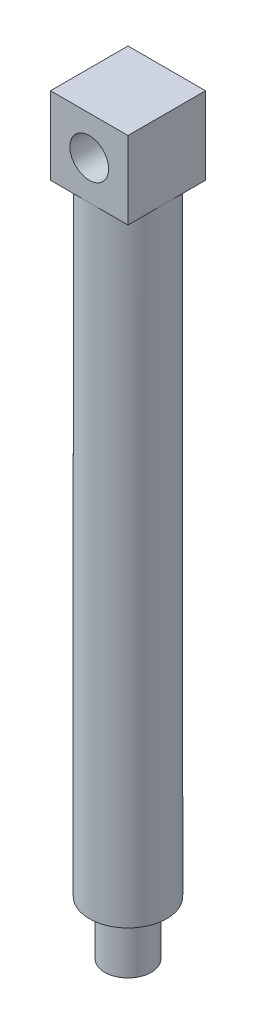
SolidWorks part; units mm, degrees
ref_plane "Front Plane" through (0, 0, 0) normal (0, 0, 1) x (1, 0, 0)
ref_plane "Top Plane" through (0, 0, 0) normal (0, 1, 0) x (1, 0, 0)
ref_plane "Right Plane" through (0, 0, 0) normal (1, 0, 0) x (0, 0, -1)
sketch "Sketch2" plane through (0, 0, 0) normal (0, 0, 1) x (1, 0, 0)
  line L0 (0, 0) -> (0, 10)
  line L1 (0, 10) -> (10, 10)
  line L2 (10, 10) -> (10, 0)
  line L3 (0, 0) -> (10, 0)
  point P6 (3.3156, 0)
  point P7 (0, 0)
  point P8 (0, 0)
  dimension "D1" = 10
  dimension "D2" = 10
extrude "Boss-Extrude2" add sketch "Sketch2" along normal blind 10 contours L2 L3 L0 L1
sketch "Sketch5" plane through (0, 0, 10) normal (0, 0, 1) x (1, 0, 0)
  circle A0 centre (5, 5) radius 2.5
  point P2 (4.9436, 5.3477)
extrude "Cut-Extrude1" cut sketch "Sketch5" against normal blind 10
sketch "Sketch6" plane through (0, 0, 0) normal (0, -1, 0) x (1, 0, 0)
  circle A0 centre (5, 5) radius 5
extrude "Boss-Extrude4" add sketch "Sketch6" along normal blind 80
sketch "Sketch7" plane through (0, -80, 0) normal (0, -1, 0) x (1, 0, 0)
  circle A0 centre (5, 5) radius 3
extrude "Boss-Extrude5" add sketch "Sketch7" along normal blind 7
